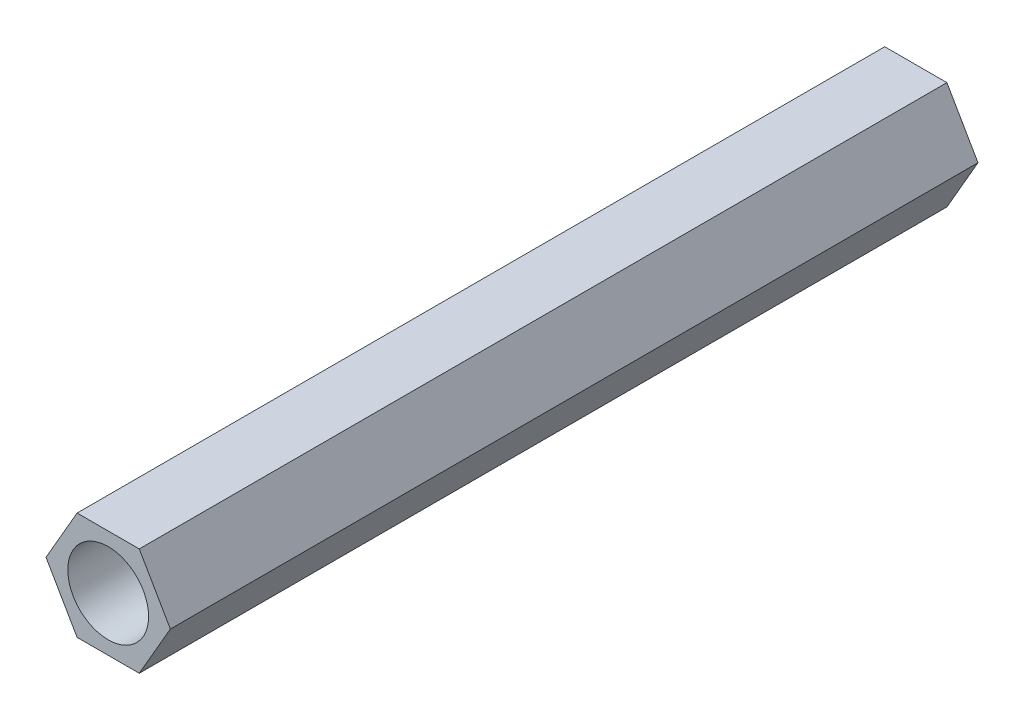
SolidWorks part; units mm, degrees
ref_plane "前视基准面" through (0, 0, 0) normal (0, 0, 1) x (1, 0, 0)
ref_plane "上视基准面" through (0, 0, 0) normal (0, 1, 0) x (1, 0, 0)
ref_plane "右视基准面" through (0, 0, 0) normal (1, 0, 0) x (0, 0, -1)
other "Configuration Table"
sketch "草图1" plane through (0, 0, 0) normal (0, 0, 1) x (1, 0, 0)
  line L1 (2.3094, 0) -> (1.1547, 2)
  line L2 (1.1547, 2) -> (-1.1547, 2)
  line L3 (-1.1547, 2) -> (-2.3094, 0)
  line L4 (-2.3094, 0) -> (-1.1547, -2)
  line L5 (-1.1547, -2) -> (1.1547, -2)
  line L6 (1.1547, -2) -> (2.3094, 0)
  circle A0 centre (0, 0) radius 2 construction
  circle A1 centre (0, 0) radius 1.5
  dimension "D1" = 2
extrude "凸台-拉伸1" add sketch "草图1" along normal blind 30
